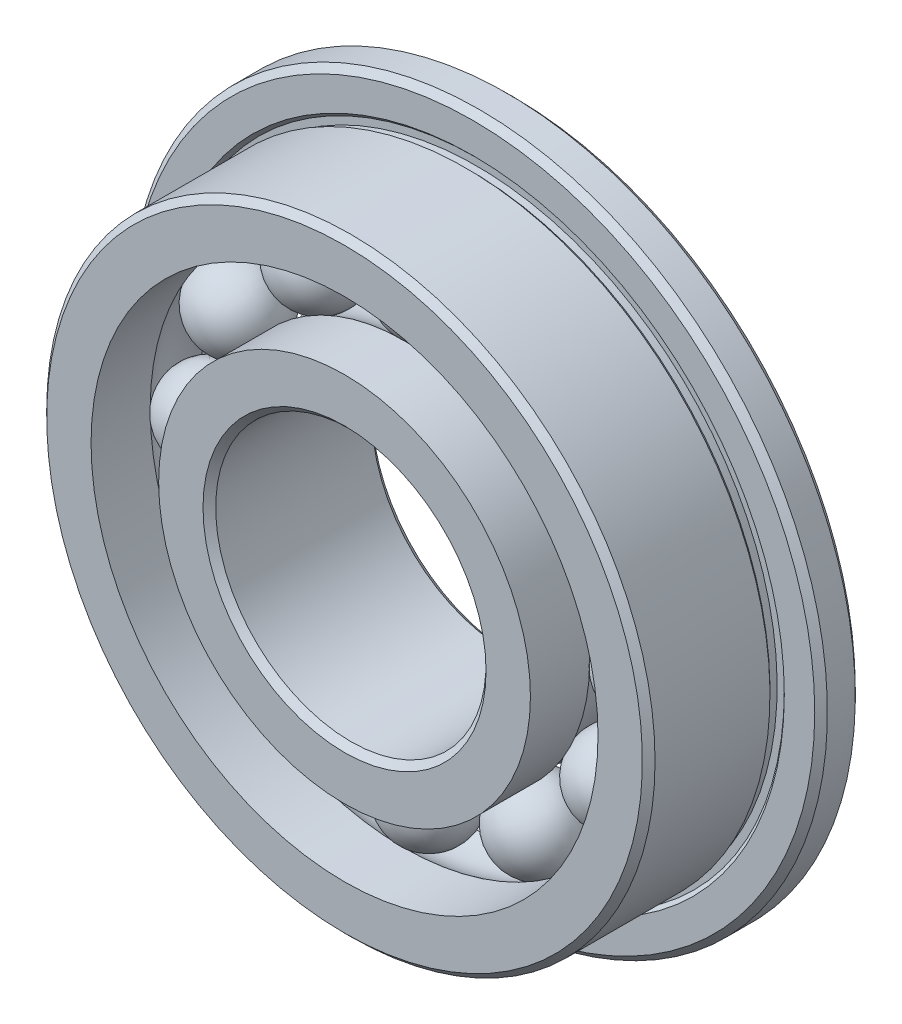
SolidWorks part; units mm, degrees
ref_plane "Front Plane" through (0, 0, 0) normal (0, 0, 1) x (1, 0, 0)
ref_plane "Top Plane" through (0, 0, 0) normal (0, 1, 0) x (1, 0, 0)
ref_plane "Right Plane" through (0, 0, 0) normal (1, 0, 0) x (0, 0, -1)
sketch "Sketch1" plane through (0, 0, 0) normal (1, 0, 0) x (0, 0, -1)
  line L0 (0, 4.5) -> (0, -4.5) construction
  line L1 (-1.25, 4.5) -> (1.25, 4.5) construction
  line L2 (0, 0) -> (1.25, 0) construction
  line L3 (1.25, 5.15) -> (1.25, -5.15) construction
  line L4 (1.25, -5.15) -> (0.65, -5.15) construction
  line L5 (1.25, 2) -> (0, 2) construction
  line L6 (1.25, 2) -> (1.25, -2) construction
  dimension "OD" = 9
  dimension "Width" = 2.5
  dimension "Flange Thickness" = 0.6
  dimension "ID" = 4
  dimension "Flange OD" = 10.3
sketch "Sketch2" plane through (0, 0, 0) normal (1, 0, 0) x (0, 0, -1)
  line L0 (1.25, 5.15) -> (0.65, 5.15)
  line L1 (0.65, 5.15) -> (0.65, 4.6061)
  line L2 (0.5439, 4.5) -> (-1.25, 4.5)
  line L3 (-1.25, 4.5) -> (-1.25, 3.75)
  line L4 (-1.25, 3.75) -> (-0.375, 3.75)
  line L5 (1.25, 5.15) -> (1.25, -5.15) construction
  line L6 (1.25, 3.75) -> (1.25, 5.15)
  line L7 (1.25, 2) -> (-1.25, 2)
  line L8 (-1.25, 2) -> (-1.25, 2.75)
  line L9 (-1.25, 2.75) -> (-0.375, 2.75)
  line L10 (1.25, 2.75) -> (1.25, 2)
  line L11 (0, 4.5) -> (0, 2) construction
  line L12 (-0.625, 3.25) -> (0.625, 3.25) construction
  line L13 (0.375, 3.75) -> (1.25, 3.75)
  line L14 (0.375, 2.75) -> (1.25, 2.75)
  line L15 (0.65, 4.6061) -> (0.703, 4.553)
  line L16 (0.703, 4.553) -> (0.703, 4.447)
  line L17 (0.703, 4.447) -> (0.597, 4.447)
  line L18 (0.597, 4.447) -> (0.5439, 4.5)
  line L19 (0.65, 4.5) -> (0.703, 4.447) construction
  line L20 (0.703, 4.553) -> (0.597, 4.447) construction
  line L21 (0.5439, 4.5) -> (0.65, 4.5) construction
  line L22 (0.65, 4.5) -> (0.65, 4.6061) construction
  circle A0 centre (0, 3.25) radius 0.625 construction
  arc A1 (-0.375, 3.75) -> (0.375, 3.75) centre (0, 3.25) cw
  arc A2 (-0.375, 2.75) -> (0.375, 2.75) centre (0, 3.25) ccw
  dimension "D1" = 2.5
  dimension "Ball Dia." = 1.25
  dimension "D2" = 135
  dimension "D3" = 0.15
  dimension "D4" = 1
  dimension "Race Thikness" = 0.75
revolve "Revolve1" add sketch "Sketch2" angle 360 about L2
fillet "Fillet1" radius 0.0938 3 edges at (0, -5.15, -1.25) (0, -5.15, -0.65) (0, -4.5, 1.25) profile chamfer
sketch "Sketch3" plane through (0, 0, 0) normal (0, 0, 1) x (1, 0, 0)
  line L0 (-2, 0) -> (2, 0) construction
  line L1 (-4.5, 0) -> (4.5, 0) construction
  point P5 (0, 0)
  dimension "ID2" = 4
  dimension "OD2" = 9
fillet "Fillet2" radius 0.0938 2 edges at (0, -2, -1.25) (0, -2, 1.25) profile chamfer
sketch "Sketch7" plane through (0, 0, 0) normal (0, 0, 1) x (1, 0, 0)
  line L0 (0, 3.875) -> (0, 2.625)
  line L1 (0, 5.15) -> (0, -5.15) construction
  line L2 (-0.7594, 3.875) -> (0, 0) construction
  line L3 (0, 0) -> (0.7594, 3.875) construction
  line L4 (0.7594, 3.875) -> (-0.7594, 3.875) construction
  circle A0 centre (0, 3.25) radius 0.625 construction
  circle A1 centre (0, 0) radius 3.875 construction
  circle A2 centre (0, 0) radius 2.625 construction
  arc A4 (0, 3.875) -> (0, 2.625) centre (0, 3.25) ccw
  dimension "D1" = 22.175
revolve "Revolve3" add sketch "Sketch7" angle 360 about L0
pattern_circular "CirPattern3" count 12 over 360 about axis through (0, 0, 0) along (0, 0, 1) of bodies 107
sketch "Sketch8" plane through (0, 0, 0) normal (1, 0, 0) x (0, 0, -1)
  line L0 (-1.25, 4.5) -> (1.25, 4.5) construction
  line L1 (1.25, 4.5) -> (1.25, 5.15) construction
  line L2 (-1.25, -4.5) -> (1.25, -4.5) construction
  line L3 (1.25, 5.15) -> (1.25, -5.15) construction
  dimension "D1" = 9
equation "\"Ball Dia.@Sketch2\" = ( \"OD@Sketch1\" - \"ID@Sketch1\" ) * .25"
equation "\"D3@Sketch2\"=\"Flange Thickness@Sketch1\"/4"
equation "\"D1@Fillet1\" = \"Race Thikness@Sketch2\" / 8"
equation "\"ID2@Sketch3\" = \"ID@Sketch1\""
equation "\"OD2@Sketch3\" = \"OD@Sketch1\""
equation "\"D1@Fillet2\" = \"Race Thikness@Sketch2\" / 8"
equation "\"D1@CirPattern3\"=360/\"D1@Sketch7\"-4"
equation "\"D4@Sketch2\" = ( \"OD@Sketch1\" - \"ID@Sketch1\" ) * .2"
